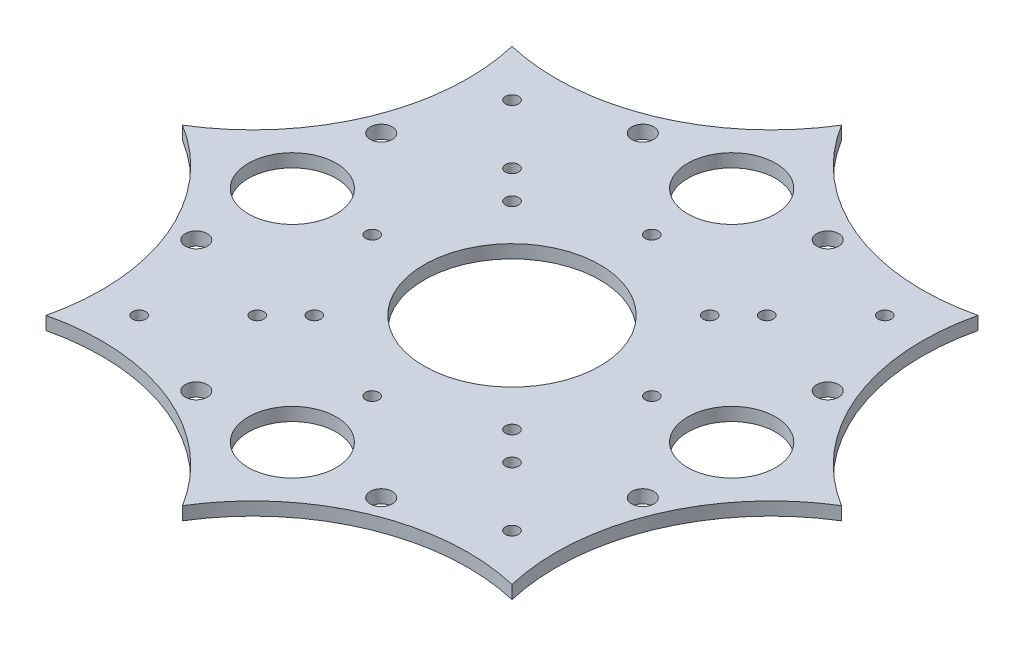
SolidWorks part; units mm, degrees
ref_plane "前基準面" through (0, 0, 0) normal (0, 0, 1) x (1, 0, 0)
ref_plane "上基準面" through (0, 0, 0) normal (0, 1, 0) x (1, 0, 0)
ref_plane "右基準面" through (0, 0, 0) normal (1, 0, 0) x (0, 0, -1)
sketch "草圖1" plane through (0, 0, 0) normal (0, 1, 0) x (1, 0, 0)
  line L0 (-53.033, 53.033) -> (53.033, -53.033) construction
  line L1 (53.033, 53.033) -> (-53.033, -53.033) construction
  line L2 (0, 0) -> (0, 75) construction
  line L3 (-28.9914, 28.9914) -> (28.9914, -28.9914) construction
  line L4 (0, 0) -> (28.9914, -28.9914) construction
  line L5 (0, 0) -> (-28.9914, -28.9914) construction
  line L6 (-75, 0) -> (75, 0) construction
  line L7 (0, -75) -> (0, 75) construction
  line L8 (-22.5, 22.5) -> (22.5, 22.5) construction
  line L9 (22.5, 22.5) -> (22.5, -22.5) construction
  line L10 (22.5, -22.5) -> (-22.5, -22.5) construction
  line L11 (-22.5, -22.5) -> (-22.5, 22.5) construction
  line L12 (0, 31.8198) -> (31.8198, 0) construction
  line L13 (31.8198, 0) -> (0, -31.8198) construction
  line L14 (0, -31.8198) -> (-31.8198, 0) construction
  line L15 (-31.8198, 0) -> (0, 31.8198) construction
  line L16 (-22.961, 55.4328) -> (0, 0) construction
  line L17 (-31.8198, 0) -> (-20, 0) construction
  line L18 (-31.8198, 0) -> (-20, 0) construction
  line L19 (-20, 0) -> (-25.9099, 0) construction
  line L20 (-25.9099, 0) -> (-25.9099, -8.1379) construction
  line L21 (20, 0) -> (31.8198, 0) construction
  line L22 (31.8198, 0) -> (25.9099, 0) construction
  line L23 (25.9099, 0) -> (25.9099, -8.1379) construction
  circle A0 centre (0, 0) radius 75 construction
  circle A1 centre (-42.4264, 42.4264) radius 1.5
  circle A2 centre (-28.9914, 28.9914) radius 1.5
  circle A3 centre (28.9914, -28.9914) radius 1.5
  circle A4 centre (42.4264, -42.4264) radius 1.5
  circle A5 centre (42.4264, 42.4264) radius 1.5
  circle A6 centre (28.9914, 28.9914) radius 1.5
  circle A7 centre (-28.9914, -28.9914) radius 1.5
  circle A8 centre (-42.4264, -42.4264) radius 1.5
  circle A9 centre (42.4264, -42.4264) radius 1.5
  circle A10 centre (28.9914, -28.9914) radius 1.5
  circle A11 centre (-28.9914, 28.9914) radius 1.5
  circle A12 centre (-42.4264, 42.4264) radius 1.5
  circle A13 centre (-42.4264, -42.4264) radius 1.5
  circle A14 centre (-28.9914, -28.9914) radius 1.5
  circle A15 centre (28.9914, 28.9914) radius 1.5
  circle A16 centre (42.4264, 42.4264) radius 1.5
  circle A17 centre (0, 0) radius 20
  circle A18 centre (0, 31.8198) radius 1.5
  circle A19 centre (31.8198, 0) radius 1.5
  circle A20 centre (22.5, 22.5) radius 1.5
  circle A21 centre (0, -31.8198) radius 1.5
  circle A22 centre (-22.5, -22.5) radius 1.5
  circle A23 centre (-31.8198, 0) radius 1.5
  circle A24 centre (-22.5, 22.5) radius 1.5
  circle A25 centre (22.5, -22.5) radius 1.5
  arc A26 (-53.033, 53.033) -> (0, 75) centre (-41.7036, 100.6815) ccw
  arc A27 (0, 75) -> (53.033, 53.033) centre (41.7036, 100.6815) ccw
  arc A28 (53.033, 53.033) -> (75, 0) centre (100.6815, 41.7036) ccw
  arc A29 (75, 0) -> (53.033, -53.033) centre (100.6815, -41.7036) ccw
  arc A30 (53.033, -53.033) -> (0, -75) centre (41.7036, -100.6815) ccw
  arc A31 (0, -75) -> (-53.033, -53.033) centre (-41.7036, -100.6815) ccw
  arc A32 (-53.033, -53.033) -> (-75, 0) centre (-100.6815, -41.7036) ccw
  arc A33 (-75, 0) -> (-53.033, 53.033) centre (-100.6815, 41.7036) ccw
  circle A34 centre (-21.0476, 50.8134) radius 2.5
  circle A39 centre (21.0476, 50.8134) radius 2.5
  circle A40 centre (50.8134, 21.0476) radius 2.5
  circle A41 centre (50.8134, -21.0476) radius 2.5
  circle A42 centre (21.0476, -50.8134) radius 2.5
  circle A43 centre (-21.0476, -50.8134) radius 2.5
  circle A44 centre (-50.8134, -21.0476) radius 2.5
  circle A45 centre (-50.8134, 21.0476) radius 2.5
  circle A46 centre (0, 50) radius 10
  circle A47 centre (50, 0) radius 10
  circle A48 centre (0, -50) radius 10
  circle A49 centre (-50, 0) radius 10
  dimension "D2" = 3
  dimension "D3" = 3
  dimension "D4" = 3
  dimension "D5" = 3
  dimension "D9" = 150
  dimension "D12" = 40
  dimension "D14" = 3
  dimension "D16" = 5
  dimension "D18" = 8
  dimension "D24" = 20
  dimension "D1" = 45
  dimension "D6" = 19
  dimension "D7" = 19
  dimension "D8" = 120
  dimension "D11" = 90
  dimension "D13" = 45
  dimension "D15" = 45
  dimension "D17" = 5
  dimension "D19" = 60
  dimension "D23" = 50
  dimension "D10" = 4
extrude "填料-伸長2" add sketch "草圖1" along normal blind 3
